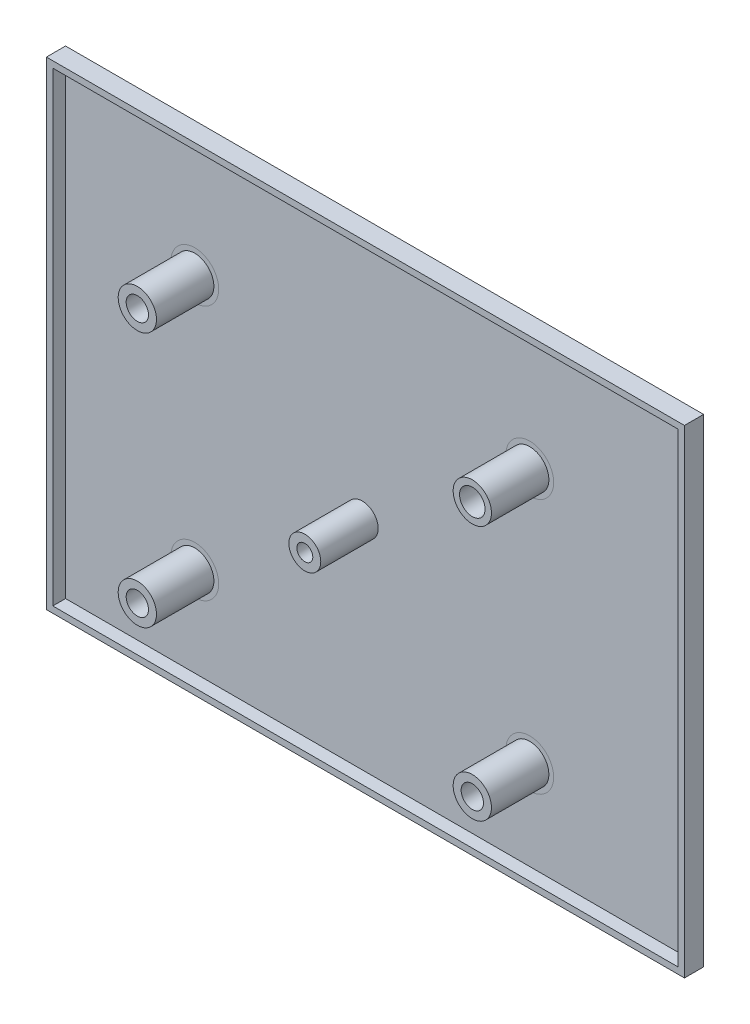
SolidWorks part; units mm, degrees
ref_plane "Plan de face" through (0, 0, 0) normal (0, 0, 1) x (1, 0, 0)
ref_plane "Plan de dessus" through (0, 0, 0) normal (0, 1, 0) x (1, 0, 0)
ref_plane "Plan de droite" through (0, 0, 0) normal (1, 0, 0) x (0, 0, -1)
sketch "Esquisse1" plane through (0, 0, 0) normal (0, 0, 1) x (1, 0, 0)
  line L0 (0, 0) -> (200, 0)
  line L1 (200, 0) -> (200, -150)
  line L2 (200, -150) -> (0, -150)
  line L3 (0, -150) -> (0, 0)
  dimension "D1" = 150
  dimension "D2" = 200
extrude "Boss.-Extru.1" add sketch "Esquisse1" along normal blind 2
sketch "Esquisse2" plane through (0, 0, 0) normal (0, 0, 1) x (1, 0, 0)
  line L0 (0, -150) -> (200, -150) construction
  line L1 (0, 0) -> (0, -150) construction
  line L2 (200, -150) -> (200, 0) construction
  circle A0 centre (42.5, -120) radius 6
  circle A1 centre (42.5, -40) radius 6
  circle A2 centre (147.5, -120) radius 6
  circle A3 centre (147.5, -40) radius 6
  circle A4 centre (95, -80) radius 5
  dimension "D1" = 30
  dimension "D2" = 42.5
  dimension "D3" = 147.5
  dimension "D4" = 30
  dimension "D5" = 80
  dimension "D6" = 80
  dimension "D7" = 105
  dimension "D8" = 70
  dimension "D9" = 105
extrude "Boss.-Extru.3" add sketch "Esquisse2" along normal blind 20 contours A1 | A3 | A4 | A0 | A2
sketch "Esquisse3" plane through (0, 0, 2) normal (0, 0, 1) x (1, 0, 0)
  line L0 (200, 0) -> (0, 0) construction
  line L1 (200, 0) -> (0, 0)
  line L2 (200, -150) -> (200, 0) construction
  line L3 (200, -150) -> (200, 0)
  line L4 (0, -150) -> (200, -150) construction
  line L5 (0, -150) -> (200, -150)
  line L6 (0, 0) -> (0, -150) construction
  line L7 (0, 0) -> (0, -150)
  line L8 (198, -148) -> (198, -2)
  line L9 (198, -2) -> (2, -2)
  line L10 (2, -2) -> (2, -148)
  line L11 (2, -148) -> (198, -148)
  dimension "D1" = 2
extrude "Boss.-Extru.4" add sketch "Esquisse3" along normal blind 4
sketch "Esquisse4" plane through (0, 0, 20) normal (0, 0, 1) x (1, 0, 0)
  circle A2 centre (147.5, -40) radius 4
  circle A3 centre (147.5, -40) radius 4
  dimension "D1" = 2
extrude "Enlèv. mat.-Extru.1" cut sketch "Esquisse4" against normal up to surface (18 mm away) up to face at (100, -75, 2)
sketch "Esquisse5" plane through (0, 0, 2) normal (0, 0, 1) x (1, 0, 0)
  circle A0 centre (42.5, -40) radius 3.5
extrude "Enlèv. mat.-Extru.4" cut sketch "Esquisse5" against normal up to surface (18 mm away) from surface at 18 up to face at (100, -75, 2) starting at face at (48.5, -40, 20)
sketch "Esquisse6" plane through (0, 0, 2) normal (0, 0, 1) x (1, 0, 0)
  circle A1 centre (147.5, -120) radius 3.5
extrude "Enlèv. mat.-Extru.6" cut sketch "Esquisse6" against normal up to surface (18 mm away) from surface at 18 up to face at (100, -75, 2) starting at face at (153.5, -120, 20)
sketch "Esquisse7" plane through (0, 0, 2) normal (0, 0, 1) x (1, 0, 0)
  circle A0 centre (42.5, -120) radius 3.5
extrude "Enlèv. mat.-Extru.7" cut sketch "Esquisse7" against normal up to surface (18 mm away) from surface at 18 up to face at (100, -75, 2) starting at face at (48.5, -120, 20)
sketch "Esquisse8" plane through (0, 0, 2) normal (0, 0, 1) x (1, 0, 0)
  circle A0 centre (95, -80) radius 2.5
extrude "Enlèv. mat.-Extru.8" cut sketch "Esquisse8" against normal up to surface (18 mm away) from surface at 18 up to face at (100, -75, 2) starting at face at (100, -80, 20)
sketch "Esquisse9" plane through (0, 0, 2) normal (0, 0, 1) x (1, 0, 0)
  line L0 (200, -150) -> (200, 0) construction
  line L1 (0, -150) -> (200, -150) construction
  line L2 (0, 0) -> (0, -150) construction
  line L3 (200, -150) -> (200, 0)
  line L4 (0, -150) -> (200, -150)
  line L5 (0, 0) -> (0, -150)
  line L6 (2, 0) -> (2, -148)
  line L7 (2, -148) -> (198, -148)
  line L8 (198, -148) -> (198, 0)
  circle A0 centre (147.5, -40) radius 6 construction
  circle A1 centre (147.5, -40) radius 6
  circle A2 centre (147.5, -40) radius 7.5
  dimension "D1" = 1.5
  dimension "D2" = 2
sketch "Esquisse10" plane through (0, 0, 0) normal (0, 0, 1) x (1, 0, 0)
  circle A1 centre (147.5, -120) radius 6 construction
  circle A2 centre (147.5, -120) radius 6
  circle A3 centre (147.5, -40) radius 6 construction
  circle A4 centre (147.5, -40) radius 6
  circle A5 centre (147.5, -40) radius 7.5
  circle A6 centre (42.5, -40) radius 6 construction
  circle A7 centre (42.5, -40) radius 6
  circle A8 centre (42.5, -120) radius 6 construction
  circle A9 centre (42.5, -120) radius 6
  circle A10 centre (42.5, -40) radius 7.5
  circle A11 centre (42.5, -120) radius 7.5
  circle A12 centre (147.5, -120) radius 7.5
  dimension "D1" = 1.5
  dimension "D2" = 1.5
  dimension "D3" = 1.5
sketch "Esquisse11" plane through (0, 0, 0) normal (0, 0, 1) x (1, 0, 0)
  line L4 (200, -150) -> (200, 0)
  line L5 (200, 0) -> (0, 0)
  line L6 (0, 0) -> (0, -150)
  line L7 (0, -150) -> (200, -150)
  line L8 (200, -150) -> (200, 0)
  line L9 (200, 0) -> (0, 0)
  line L10 (0, 0) -> (0, -150)
  line L11 (0, -150) -> (200, -150)
  circle A0 centre (42.5, -40) radius 7.5 construction
  circle A1 centre (42.5, -40) radius 6 construction
  circle A2 centre (42.5, -40) radius 7.5
  circle A3 centre (42.5, -40) radius 6
  circle A4 centre (147.5, -40) radius 6 construction
  circle A5 centre (147.5, -40) radius 7.5 construction
  circle A6 centre (147.5, -40) radius 6
  circle A7 centre (147.5, -40) radius 7.5
  circle A8 centre (147.5, -120) radius 6 construction
  circle A9 centre (147.5, -120) radius 7.5 construction
  circle A10 centre (147.5, -120) radius 6
  circle A11 centre (147.5, -120) radius 7.5
  circle A12 centre (42.5, -120) radius 7.5 construction
  circle A13 centre (42.5, -120) radius 6 construction
  circle A14 centre (42.5, -120) radius 7.5
  circle A15 centre (42.5, -120) radius 6
  dimension "D1" = 0
split line "Ligne de séparation1"
